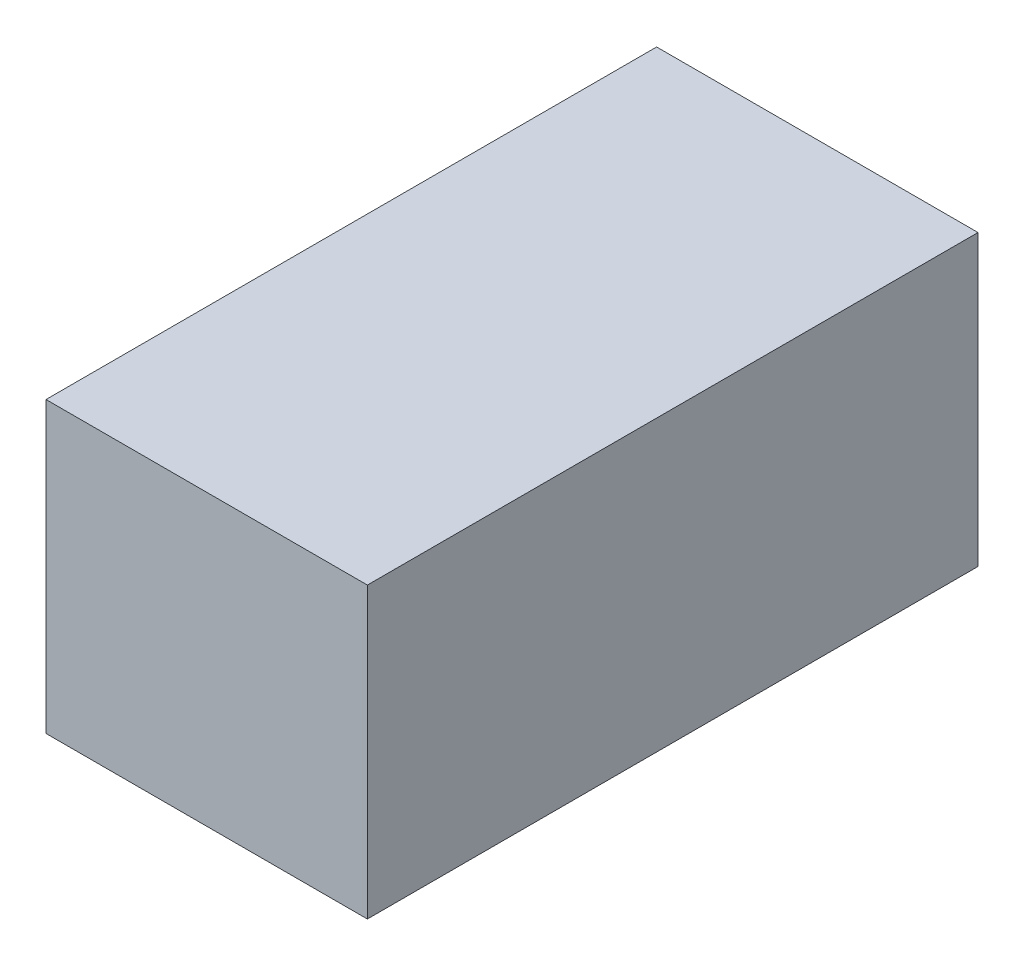
SolidWorks part; units mm, degrees
ref_plane "Front Plane" through (0, 0, 0) normal (0, 0, 1) x (1, 0, 0)
ref_plane "Top Plane" through (0, 0, 0) normal (0, 1, 0) x (1, 0, 0)
ref_plane "Right Plane" through (0, 0, 0) normal (1, 0, 0) x (0, 0, -1)
other "Center of Mass"
sketch "Sketch1" plane through (0, 0, 0) normal (0, 1, 0) x (1, 0, 0)
  line L1 (-25, -47.5) -> (25, -47.5)
  line L2 (-25, -47.5) -> (-25, 47.5)
  line L3 (-25, 47.5) -> (25, 47.5)
  line L4 (25, -47.5) -> (25, 47.5)
  line L5 (-25, -47.5) -> (25, 47.5) construction
  line L6 (-25, 47.5) -> (25, -47.5) construction
  point P0 (0, 0)
  dimension "D1" = 50
  dimension "D2" = 95
extrude "Boss-Extrude1" add sketch "Sketch1" along normal blind 45
sketch "Sketch2" plane through (0, 0, -47.5) normal (0, 0, -1) x (-1, 0, 0)
  line L0 (-25, 22.5) -> (0, 22.5) construction
  line L1 (-25, 45) -> (-25, 0) construction
  line L2 (0, 22.5) -> (0, 0) construction
  circle A0 centre (0, 22.5) radius 20
  point P7 (0, 25.1389)
  dimension "D1" = 40
extrude "Cut-Extrude1" cut sketch "Sketch2" against normal blind 5
